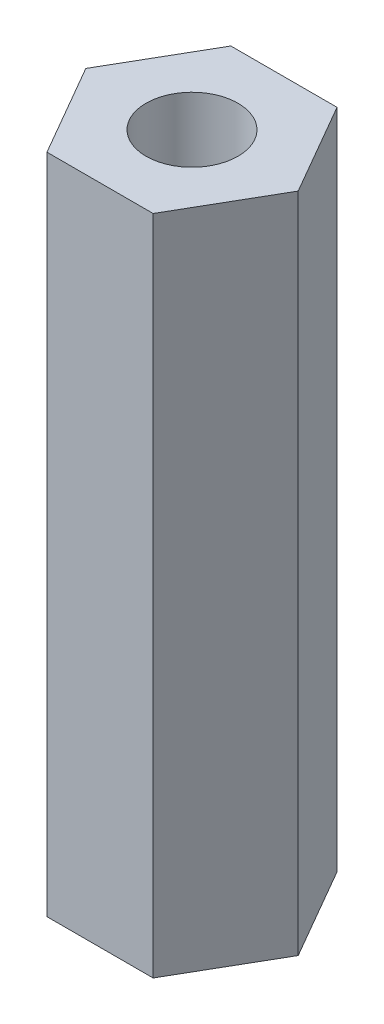
SolidWorks part; units mm, degrees
ref_plane "前视基准面" through (0, 0, 0) normal (0, 0, 1) x (1, 0, 0)
ref_plane "上视基准面" through (0, 0, 0) normal (0, 1, 0) x (1, 0, 0)
ref_plane "右视基准面" through (0, 0, 0) normal (1, 0, 0) x (0, 0, -1)
sketch "草图1" plane through (0, 0, 0) normal (0, 1, 0) x (1, 0, 0)
  line L1 (1.4434, -2.5) -> (2.8868, 0)
  line L2 (2.8868, 0) -> (1.4434, 2.5)
  line L3 (1.4434, 2.5) -> (-1.4434, 2.5)
  line L4 (-1.4434, 2.5) -> (-2.8868, 0)
  line L5 (-2.8868, 0) -> (-1.4434, -2.5)
  line L6 (-1.4434, -2.5) -> (1.4434, -2.5)
  circle A0 centre (0, 0) radius 2.5 construction
  circle A1 centre (0, 0) radius 1.25
  dimension "D2" = 2.5
  dimension "D1" = 5
extrude "凸台-拉伸1" add sketch "草图1" along normal blind 18
